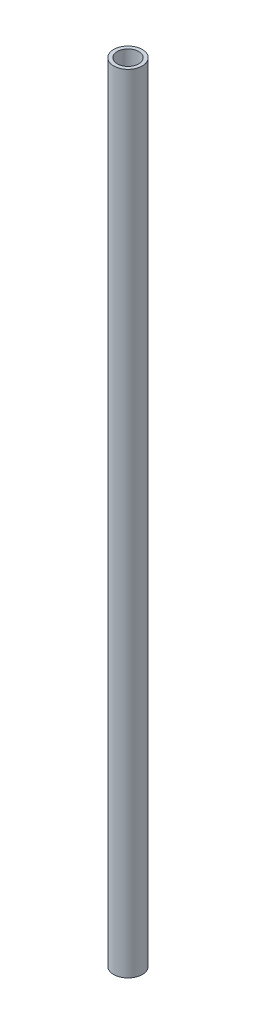
SolidWorks part; units mm, degrees
ref_plane "Front Plane" through (0, 0, 0) normal (0, 0, 1) x (1, 0, 0)
ref_plane "Top Plane" through (0, 0, 0) normal (0, 1, 0) x (1, 0, 0)
ref_plane "Right Plane" through (0, 0, 0) normal (1, 0, 0) x (0, 0, -1)
sketch "Sketch1" plane through (0, 0, 0) normal (0, 0, 1) x (1, 0, 0)
  line L0 (0, 0) -> (0, 220)
  point P6 (0, 220)
  dimension "D1" = 220
sketch "Sketch2" plane through (0, 0, 0) normal (0, 1, 0) x (1, 0, 0)
  circle A0 centre (0, 0) radius 4
  circle A1 centre (0, 0) radius 3
  dimension "D1" = 6
  dimension "D2" = 8
sweep "Sweep1" add profiles "Sketch2" path "Sketch1"
